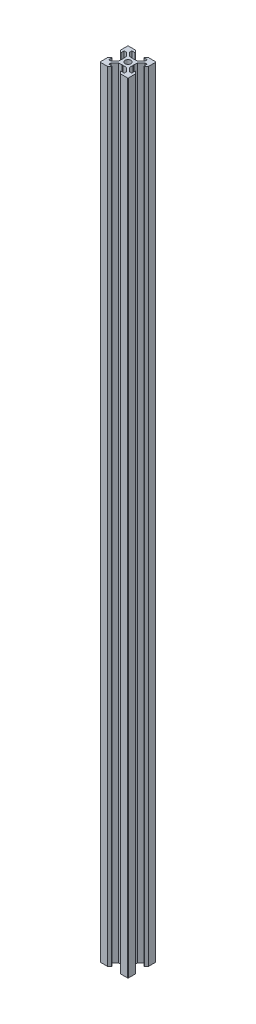
SolidWorks part; units mm, degrees
ref_plane "Front Plane" through (0, 0, 0) normal (0, 0, 1) x (1, 0, 0)
ref_plane "Top Plane" through (0, 0, 0) normal (0, 1, 0) x (1, 0, 0)
ref_plane "Right Plane" through (0, 0, 0) normal (1, 0, 0) x (0, 0, -1)
sketch "Sketch1" plane through (0, 0, 0) normal (0, 1, 0) x (1, 0, 0)
  line L0 (0, 20) -> (20, 0) construction
  line L1 (20, 5.42) -> (20, 0.5)
  line L2 (18.4507, 6.875) -> (20, 5.42)
  line L3 (18.2007, 6.875) -> (18.4507, 6.875)
  line L4 (18.2007, 6.875) -> (18.2007, 4.5)
  line L5 (20, 20) -> (0, 0) construction
  line L6 (15.5, 16.5607) -> (12.84, 13.9007)
  line L7 (16.5607, 15.5) -> (13.9007, 12.84)
  line L8 (10, 10) -> (20, 10) construction
  line L9 (10, 10) -> (10, 20) construction
  line L10 (13.9007, 10.25) -> (13.9007, 12.84)
  line L11 (10.25, 13.9007) -> (12.84, 13.9007)
  line L12 (10, 13.6507) -> (10.25, 13.9007)
  line L13 (13.9007, 10.25) -> (13.6507, 10)
  line L14 (13.125, 18.2007) -> (15.5, 18.2007)
  line L15 (18.2007, 15.5) -> (18.2007, 13.13)
  line L16 (13.125, 18.2007) -> (13.125, 18.4507)
  line L17 (18.2007, 13.13) -> (18.4507, 13.13)
  line L18 (13.125, 18.4507) -> (14.58, 20)
  line L19 (18.4507, 13.13) -> (20, 14.58)
  line L20 (14.58, 20) -> (19.5, 20)
  line L21 (20, 14.58) -> (20, 19.5)
  line L22 (15.5, 18.2007) -> (15.5, 16.5607)
  line L23 (16.5607, 15.5) -> (18.2007, 15.5)
  line L24 (18.2007, 4.5) -> (16.5607, 4.5)
  line L25 (16.5607, 4.5) -> (13.9007, 7.16)
  line L26 (13.9007, 9.75) -> (13.9007, 7.16)
  line L27 (13.6507, 10) -> (13.9007, 9.75)
  line L28 (10.25, 6.0993) -> (10, 6.3493)
  line L29 (10.25, 6.0993) -> (12.84, 6.0993)
  line L30 (15.5, 3.4393) -> (12.84, 6.0993)
  line L31 (15.5, 3.4393) -> (15.5, 1.7993)
  line L32 (15.5, 1.7993) -> (13.13, 1.7993)
  line L33 (13.13, 1.7993) -> (13.13, 1.5493)
  line L34 (13.13, 1.5493) -> (14.58, 0)
  line L35 (14.58, 0) -> (19.5, 0)
  line L36 (5.42, 0) -> (0.5, 0)
  line L37 (6.875, 1.5493) -> (5.42, 0)
  line L38 (6.875, 1.7993) -> (6.875, 1.5493)
  line L39 (6.875, 1.7993) -> (4.5, 1.7993)
  line L40 (4.5, 1.7993) -> (4.5, 3.4393)
  line L41 (4.5, 3.4393) -> (7.16, 6.0993)
  line L42 (9.75, 6.0993) -> (7.16, 6.0993)
  line L43 (10, 6.3493) -> (9.75, 6.0993)
  line L44 (6.0993, 9.75) -> (6.3493, 10)
  line L45 (6.0993, 9.75) -> (6.0993, 7.16)
  line L46 (3.4393, 4.5) -> (6.0993, 7.16)
  line L47 (3.4393, 4.5) -> (1.7993, 4.5)
  line L48 (1.7993, 4.5) -> (1.7993, 6.87)
  line L49 (1.7993, 6.87) -> (1.5493, 6.87)
  line L50 (1.5493, 6.87) -> (0, 5.42)
  line L51 (0, 5.42) -> (0, 0.5)
  line L52 (0, 14.58) -> (0, 19.5)
  line L53 (1.5493, 13.125) -> (0, 14.58)
  line L54 (1.7993, 13.125) -> (1.5493, 13.125)
  line L55 (1.7993, 13.125) -> (1.7993, 15.5)
  line L56 (1.7993, 15.5) -> (3.4393, 15.5)
  line L57 (3.4393, 15.5) -> (6.0993, 12.84)
  line L58 (6.0993, 10.25) -> (6.0993, 12.84)
  line L59 (6.3493, 10) -> (6.0993, 10.25)
  line L60 (9.75, 13.9007) -> (10, 13.6507)
  line L61 (9.75, 13.9007) -> (7.16, 13.9007)
  line L62 (4.5, 16.5607) -> (7.16, 13.9007)
  line L63 (4.5, 16.5607) -> (4.5, 18.2007)
  line L64 (4.5, 18.2007) -> (6.87, 18.2007)
  line L65 (6.87, 18.2007) -> (6.87, 18.4507)
  line L66 (6.87, 18.4507) -> (5.42, 20)
  line L67 (5.42, 20) -> (0.5, 20)
  arc A0 (12.1, 10) -> (10, 12.1) centre (10, 10) ccw
  arc A1 (19.5, 20) -> (20, 19.5) centre (19.5, 19.5) cw
  arc A2 (10, 7.9) -> (12.1, 10) centre (10, 10) ccw
  arc A3 (20, 0.5) -> (19.5, 0) centre (19.5, 0.5) cw
  arc A4 (7.9, 10) -> (10, 7.9) centre (10, 10) ccw
  arc A5 (0.5, 0) -> (0, 0.5) centre (0.5, 0.5) cw
  arc A6 (10, 12.1) -> (7.9, 10) centre (10, 10) ccw
  arc A7 (0, 19.5) -> (0.5, 20) centre (0.5, 19.5) cw
  point P95 (10, 10)
  dimension "D3" = 1.5
  dimension "D4" = 4.2
  dimension "D20" = 0.5
  dimension "D1" = 20
  dimension "D2" = 20
  dimension "D5" = 4
  dimension "D7" = 0.25
  dimension "D8" = 0.25
  dimension "D9" = 4.3
  dimension "D10" = 4.3
  dimension "D11" = 3.125
  dimension "D12" = 3.13
  dimension "D13" = 4.58
  dimension "D14" = 0.25
  dimension "D15" = 4.58
  dimension "D16" = 0.25
  dimension "D17" = 5.5
  dimension "D18" = 5.5
  dimension "D19" = 0.25
extrude "Boss-Extrude1" add sketch "Sketch1" along normal blind 555
